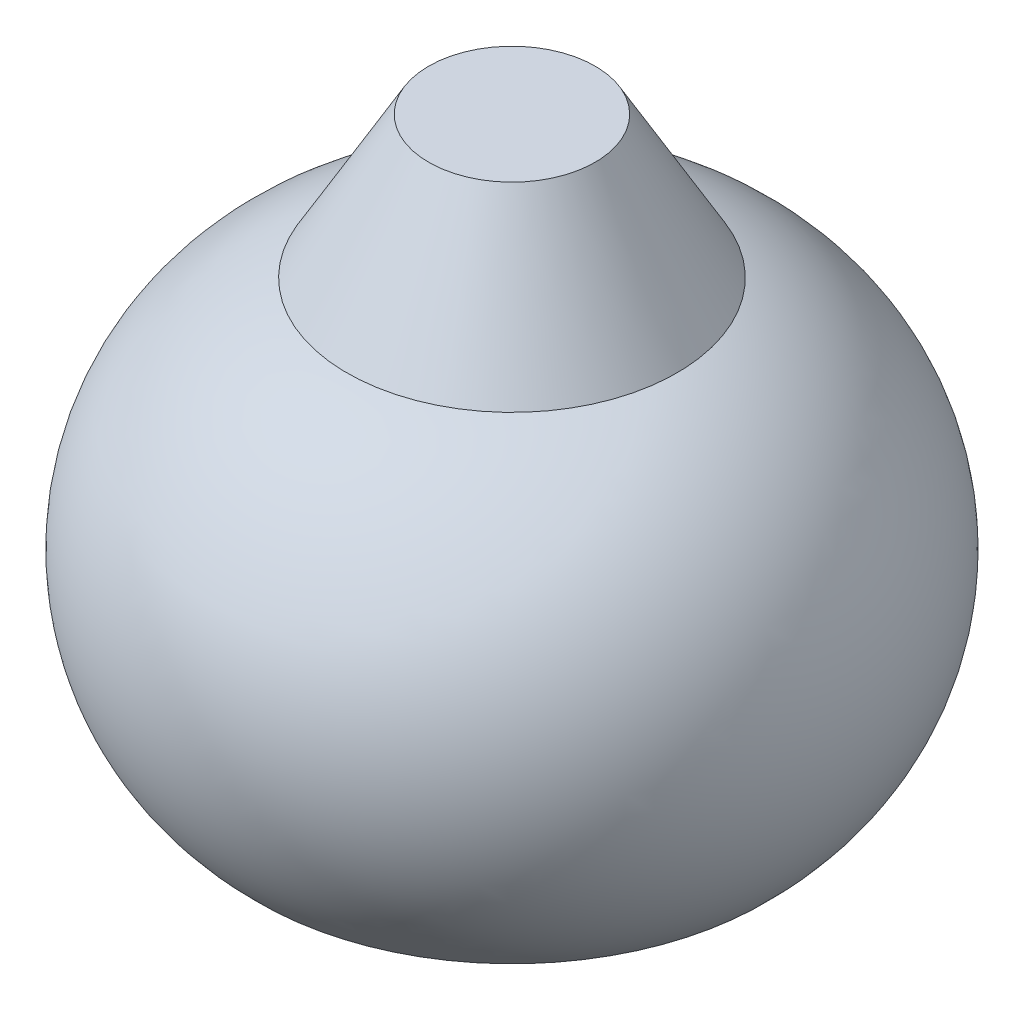
SolidWorks part; units mm, degrees
ref_plane "前视基准面" through (0, 0, 0) normal (0, 0, 1) x (1, 0, 0)
ref_plane "上视基准面" through (0, 0, 0) normal (0, 1, 0) x (1, 0, 0)
ref_plane "右视基准面" through (0, 0, 0) normal (1, 0, 0) x (0, 0, -1)
other "Configuration Table"
sketch "草图7" plane through (0, 0, 0) normal (0, 0, 1) x (1, 0, 0)
  line L0 (0, 0) -> (-30, 0) construction
  line L1 (0, 23.2197) -> (0, -23.2197)
  line L2 (0, 23.2197) -> (-10, 23.2197)
  line L3 (-10, 23.2197) -> (-19.815, 6.2197)
  line L9 (-19.815, -23.2197) -> (-19.815, -46.7803)
  line L10 (0, -23.2197) -> (-19.815, -23.2197)
  line L11 (-25, -46.7803) -> (-30.1962, -43.7803)
  line L12 (-25, -46.7803) -> (-19.815, -46.7803)
  arc A0 (-19.815, 6.2197) -> (-30.1962, -43.7803) centre (-9.5846, -21.9821) ccw
  point P5 (0, 0)
  dimension "D3" = 120
  dimension "D4" = 150
  dimension "D8" = 30
  dimension "D1" = 30
  dimension "D2" = 19.815
  dimension "D5" = 10
  dimension "D6" = 17
  dimension "D7" = 70
  dimension "D9" = 25
  dimension "D10" = 6
revolve "旋转5" add sketch "草图7" angle 360 about L1
